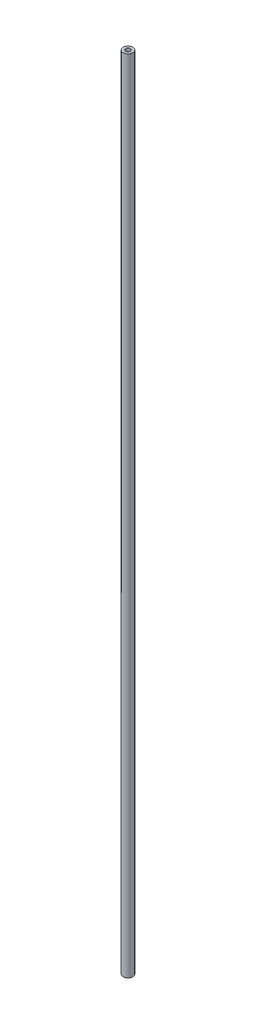
SolidWorks part; units mm, degrees
ref_plane "Front Plane" through (0, 0, 0) normal (0, 0, 1) x (1, 0, 0)
ref_plane "Top Plane" through (0, 0, 0) normal (0, 1, 0) x (1, 0, 0)
ref_plane "Right Plane" through (0, 0, 0) normal (1, 0, 0) x (0, 0, -1)
sketch "Sketch1" plane through (0, 0, 0) normal (0, 1, 0) x (1, 0, 0)
  circle A0 centre (0, 0) radius 3
  circle A1 centre (0, 0) radius 1.5
  dimension "D1" = 3
  dimension "D2" = 6
extrude "Boss-Extrude1" add sketch "Sketch1" along normal blind 500
equation "\"carbon_fiber_tube_diam\"= 1in, 25.4mm"
equation "\"clip_tube_diam\"= 6mm"
equation "\"middle_tube_len\"= 500mm"
equation "\"D1@Boss-Extrude1\"=\"middle_tube_len\""
